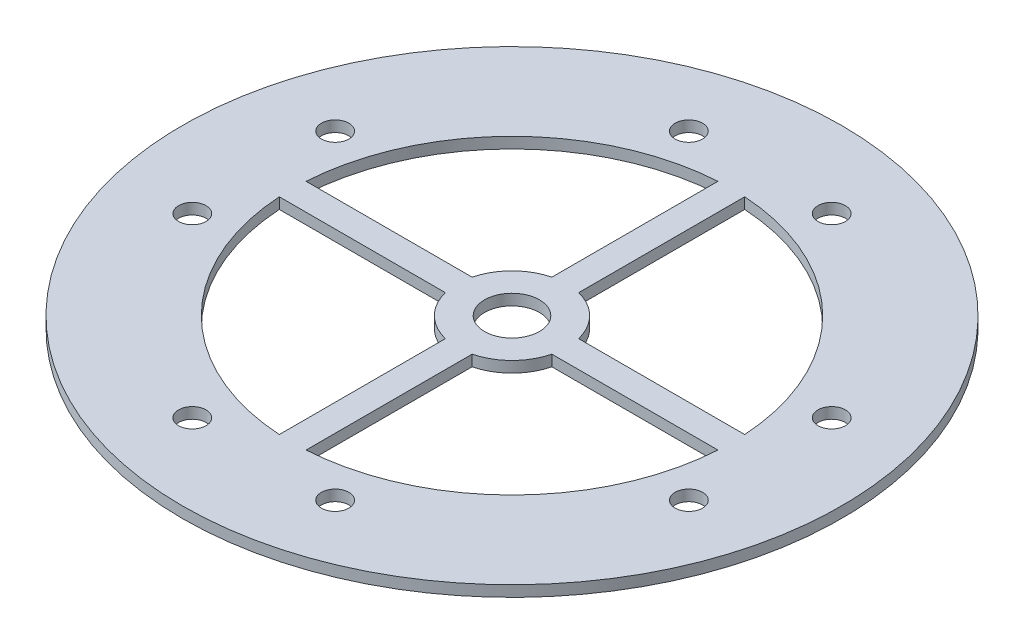
SolidWorks part; units mm, degrees
ref_plane "Front Plane" through (0, 0, 0) normal (0, 0, 1) x (1, 0, 0)
ref_plane "Top Plane" through (0, 0, 0) normal (0, 1, 0) x (1, 0, 0)
ref_plane "Right Plane" through (0, 0, 0) normal (1, 0, 0) x (0, 0, -1)
sketch "Sketch1" plane through (0, 0, 0) normal (0, 1, 0) x (1, 0, 0)
  line L0 (0, 0) -> (0, 57.404) construction
  line L1 (0, 57.404) -> (-16.51, 57.404)
  line L2 (0, 57.404) -> (16.51, 57.404)
  line L3 (-3.0994, 12.316) -> (-3.0994, 50.7054)
  line L4 (3.0994, 12.316) -> (3.0994, 50.7054)
  line L5 (12.316, 3.0994) -> (50.7054, 3.0994)
  line L6 (12.316, -3.0994) -> (50.7054, -3.0994)
  line L7 (3.0994, -12.316) -> (3.0994, -50.7054)
  line L8 (-3.0994, -12.316) -> (-3.0994, -50.7054)
  line L9 (-12.316, -3.0994) -> (-50.7054, -3.0994)
  line L10 (-12.316, 3.0994) -> (-50.7054, 3.0994)
  circle A0 centre (0, 0) radius 76.2
  arc A1 (-50.7054, -3.0994) -> (-3.0994, -50.7054) centre (0, 0) ccw
  arc A2 (-3.0994, 12.316) -> (-12.316, 3.0994) centre (0, 0) ccw
  circle A4 centre (-16.51, 57.404) radius 3.175
  circle A5 centre (16.51, 57.404) radius 3.175
  circle A6 centre (57.404, -16.51) radius 3.175
  circle A7 centre (57.404, 16.51) radius 3.175
  circle A8 centre (-16.51, -57.404) radius 3.175
  circle A9 centre (16.51, -57.404) radius 3.175
  circle A10 centre (-57.404, 16.51) radius 3.175
  circle A11 centre (-57.404, -16.51) radius 3.175
  arc A12 (12.316, 3.0994) -> (3.0994, 12.316) centre (0, 0) ccw
  arc A13 (3.0994, -12.316) -> (12.316, -3.0994) centre (0, 0) ccw
  arc A14 (-12.316, -3.0994) -> (-3.0994, -12.316) centre (0, 0) ccw
  circle A16 centre (0, 0) radius 6.35
  arc A17 (3.0994, -50.7054) -> (50.7054, -3.0994) centre (0, 0) ccw
  arc A18 (50.7054, 3.0994) -> (3.0994, 50.7054) centre (0, 0) ccw
  arc A19 (-3.0994, 50.7054) -> (-50.7054, 3.0994) centre (0, 0) ccw
  point P26 (0, 0)
  point P43 (0, 0)
  dimension "D1" = 25.4
  dimension "D2" = 101.6
  dimension "D5" = 152.4
  dimension "D6" = 16.51
  dimension "D7" = 4
  dimension "D4" = 16.51
  dimension "D8" = 38.3894
  dimension "D9" = 4
extrude "Boss-Extrude1" add sketch "Sketch1" along normal blind 2.54
